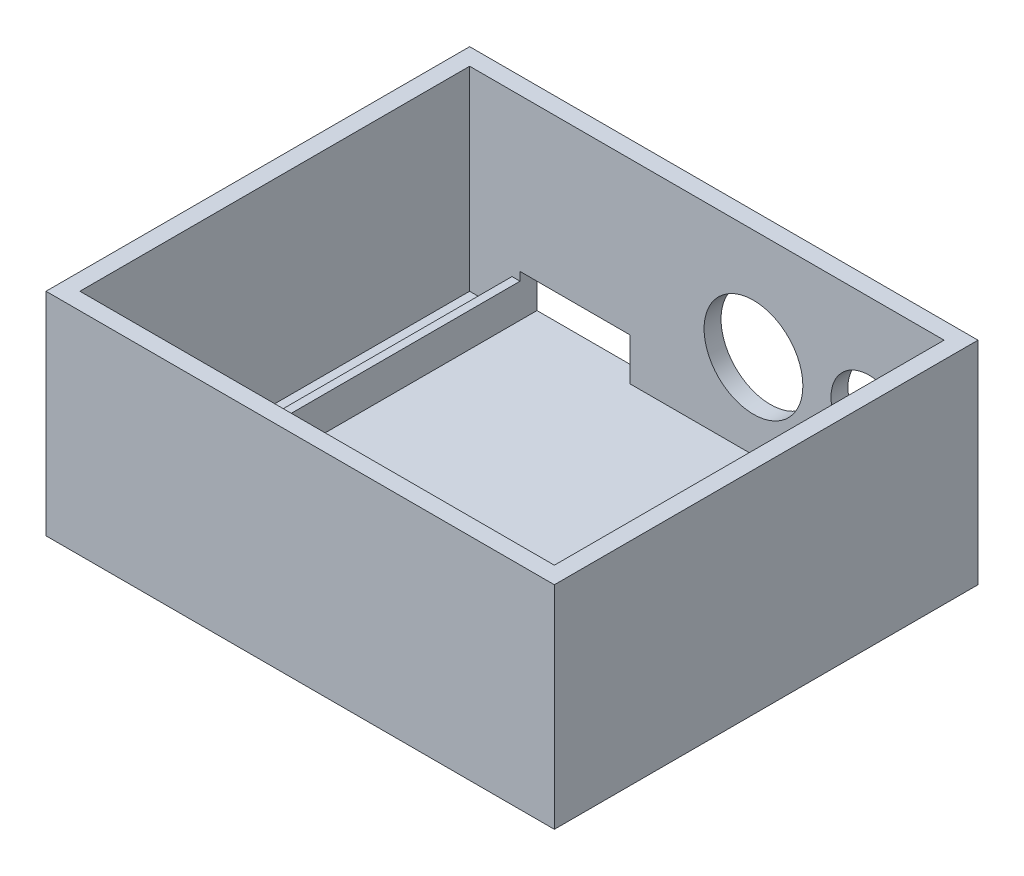
SolidWorks part; units mm, degrees
ref_plane "Front Plane" through (0, 0, 0) normal (0, 0, 1) x (1, 0, 0)
ref_plane "Top Plane" through (0, 0, 0) normal (0, 1, 0) x (1, 0, 0)
ref_plane "Right Plane" through (0, 0, 0) normal (1, 0, 0) x (0, 0, -1)
sketch "Sketch1" plane through (0, 0, 0) normal (0, 1, 0) x (1, 0, 0)
  line L1 (-70.5712, -39.9173) -> (49.4288, -39.9173)
  line L2 (-70.5712, -39.9173) -> (-70.5712, 60.0827)
  line L3 (-70.5712, 60.0827) -> (49.4288, 60.0827)
  line L4 (49.4288, -39.9173) -> (49.4288, 60.0827)
  dimension "D1" = 120
  dimension "D2" = 100
extrude "Boss-Extrude1" add sketch "Sketch1" along normal blind 50
sketch "Sketch2" plane through (0, 50, 0) normal (0, 1, 0) x (1, 0, 0)
  line L0 (49.4288, 60.0827) -> (-70.5712, 60.0827) construction
  line L1 (-66.5712, 56.0827) -> (45.4288, 56.0827)
  line L2 (-66.5712, 56.0827) -> (-66.5712, -35.9173)
  line L3 (-66.5712, -35.9173) -> (45.4288, -35.9173)
  line L4 (45.4288, 56.0827) -> (45.4288, -35.9173)
  line L5 (-70.5712, -39.9173) -> (49.4288, -39.9173) construction
  line L6 (-70.5712, 60.0827) -> (-70.5712, -39.9173) construction
  line L7 (49.4288, -39.9173) -> (49.4288, 60.0827) construction
  dimension "D1" = 4
  dimension "D2" = 4
  dimension "D3" = 4
  dimension "D4" = 4
extrude "Cut-Extrude1" cut sketch "Sketch2" against normal blind 46
sketch "Sketch3" plane through (0, 4, 0) normal (0, 1, 0) x (1, 0, 0)
  line L0 (-66.5712, 56.0827) -> (-66.5712, -35.9173) construction
  line L1 (49.4288, 60.0827) -> (-70.5712, 60.0827) construction
  line L2 (-56.5712, 60.0827) -> (-31.9712, 60.0827)
  line L3 (-56.5712, 60.0827) -> (-56.5712, -9.9173)
  line L4 (-56.5712, -9.9173) -> (-31.9712, -9.9173)
  line L5 (-31.9712, 60.0827) -> (-31.9712, -9.9173)
  dimension "D1" = 24.6
  dimension "D2" = 70
  dimension "D3" = 10
extrude "Boss-Extrude3" add sketch "Sketch3" along normal blind 8
sketch "Sketch6" plane through (0, 0, 9.9173) normal (0, 0, 1) x (1, 0, 0)
  line L0 (-56.5712, 12) -> (-31.9712, 12) construction
  line L1 (-54.6743, 12) -> (-30.0643, 12)
  line L2 (-54.6743, 12) -> (-54.6743, 4)
  line L3 (-54.6743, 4) -> (-30.0643, 4)
  line L4 (-30.0643, 12) -> (-30.0643, 4)
  line L5 (-66.5712, 4) -> (45.4288, 4) construction
  dimension "D1" = 24.61
extrude "Cut-Extrude4" cut sketch "Sketch6" against normal blind 66
sketch "Sketch7" plane through (0, 0, -56.0827) normal (0, 0, 1) x (1, 0, 0)
  line L3 (-54.6743, 4) -> (-28.6743, 4)
  line L4 (-54.6743, 4) -> (-54.6743, 14)
  line L5 (-54.6743, 14) -> (-28.6743, 14)
  line L6 (-28.6743, 4) -> (-28.6743, 14)
  dimension "D1" = 26
  dimension "D2" = 10
extrude "Cut-Extrude6" cut sketch "Sketch7" against normal blind 66
sketch "Sketch8" plane through (0, 0, -56.0827) normal (0, 0, 1) x (1, 0, 0)
  line L6 (45.4288, 50) -> (-66.5712, 50) construction
  line L7 (-66.5712, 4) -> (-66.5712, 50) construction
  circle A0 centre (0.4288, 24) radius 11.6622
  dimension "D5" = 26
  dimension "D6" = 67
sketch "Sketch10" plane through (0, 0, -60.0827) normal (0, 0, -1) x (-1, 0, 0)
  line L0 (-49.4288, 50) -> (-49.4288, 0) construction
  line L2 (-50.6638, 25) -> (89.3617, 25) construction
  circle A0 centre (-27.7288, 25) radius 9
  dimension "D1" = 21.7
extrude "Cut-Extrude9" cut sketch "Sketch10" against normal blind 12.5
extrude "Cut-Extrude10" cut sketch "Sketch8" against normal blind 10
